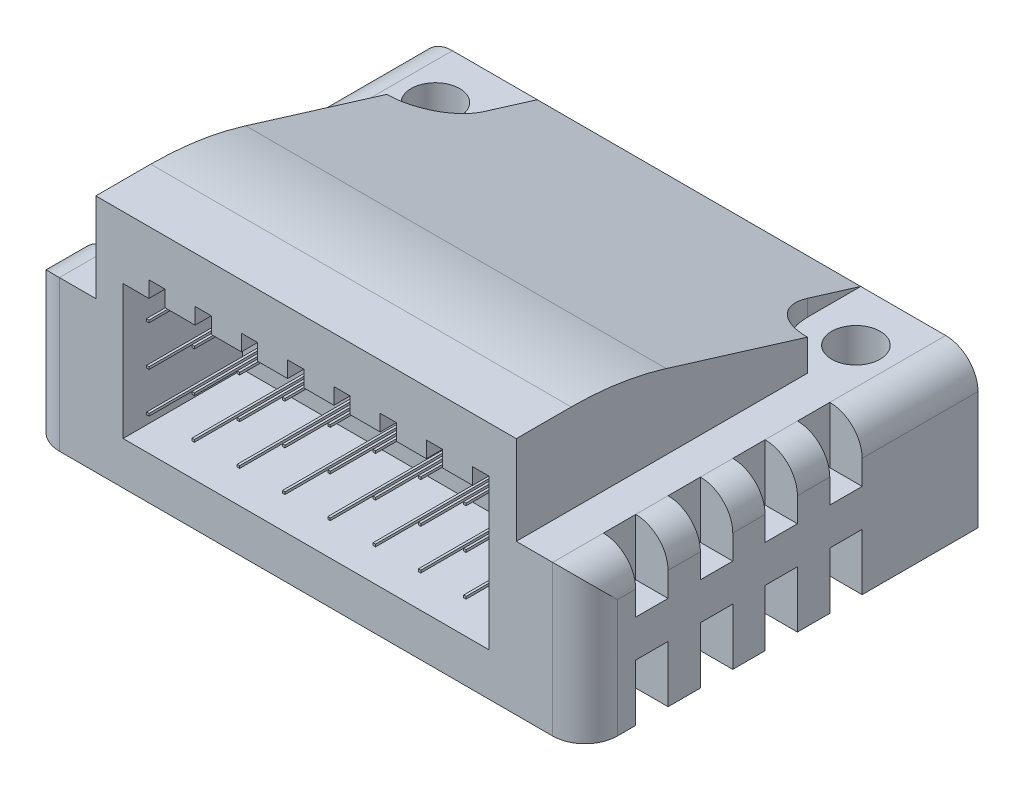
SolidWorks part; units mm, degrees
ref_plane "Front Plane" through (0, 0, 0) normal (0, 0, 1) x (1, 0, 0)
ref_plane "Top Plane" through (0, 0, 0) normal (0, 1, 0) x (1, 0, 0)
ref_plane "Right Plane" through (0, 0, 0) normal (1, 0, 0) x (0, 0, -1)
sketch "Sketch1" plane through (0, 0, 0) normal (0, 1, 0) x (1, 0, 0)
  line L1 (17.25, -12.15) -> (-17.25, -12.15)
  line L2 (17.25, -12.15) -> (17.25, 12.15)
  line L3 (17.25, 12.15) -> (-17.25, 12.15)
  line L4 (-17.25, -12.15) -> (-17.25, 12.15)
  line L5 (17.25, -12.15) -> (-17.25, 12.15) construction
  line L6 (17.25, 12.15) -> (-17.25, -12.15) construction
  point P0 (0, 0)
  dimension "D1" = 34.5
  dimension "D2" = 24.3
extrude "Boss-Extrude1" add sketch "Sketch1" along normal blind 9.3
ref_plane "Plane1" through (13, 0, 0) normal (1, 0, 0) x (0, 0, -1)
sketch "Sketch2" plane through (13, 0, 0) normal (1, 0, 0) x (0, 0, -1)
  line L0 (-12.15, 9.3) -> (12.15, 9.3) construction
  line L1 (-12.15, 9.3) -> (12.15, 9.3)
  line L2 (-12.15, 9.3) -> (-12.15, 14.8)
  line L3 (-12.15, 14.8) -> (-5.75, 14.8)
  line L4 (-5.75, 14.8) -> (12.15, 9.3)
  line L5 (-12.15, 0) -> (12.15, 0) construction
  dimension "D1" = 14.8
  dimension "D2" = 6.4
extrude "Boss-Extrude2" add sketch "Sketch2" against normal offset from surface (26 mm away) 4.25 up to face at (-17.25, 4.65, 0)
fillet "Fillet1" radius 2 4 edges at (17.25, 4.65, 12.15) (-17.25, 4.65, 12.15) (-17.25, 9.3, 0) (17.25, 9.3, 0)
fillet "Fillet2" radius 20 1 edges at (0, 14.8, 5.75)
sketch "Sketch4" plane through (17.25, 0, 0) normal (1, 0, 0) x (0, 0, -1)
  line L0 (-12.15, 0) -> (-12.15, 9.3) construction
  line L1 (-12.15, 0) -> (-12.15, 9.3)
  line L2 (-12.15, 9.3) -> (12.15, 9.3) construction
  line L3 (-12.15, 9.3) -> (12.15, 9.3)
  line L4 (12.15, 7.3) -> (12.15, 9.3) construction
  line L5 (12.15, 7.3) -> (12.15, 0) construction
  line L6 (-10.15, 0) -> (12.15, 0) construction
  line L7 (-12.15, 0) -> (-10.15, 0) construction
  line L8 (12.15, 7.3) -> (12.15, 9.3)
  line L9 (12.15, 7.3) -> (12.15, 0)
  line L10 (-10.15, 0) -> (12.15, 0)
  line L11 (-12.15, 0) -> (-10.15, 0)
  line L12 (-12.15, 4.65) -> (12.15, 4.65) construction
  line L13 (-9.0144, 9.3) -> (-9.0144, 5.8)
  line L14 (-9.0144, 5.8) -> (-7.0144, 5.8)
  line L15 (-7.0144, 5.8) -> (-7.0144, 9.3)
  line L16 (-5.0144, 9.3) -> (-5.0144, 5.8)
  line L17 (-5.0144, 5.8) -> (-3.0144, 5.8)
  line L18 (-3.0144, 5.8) -> (-3.0144, 9.3)
  line L19 (-1.0144, 9.3) -> (-1.0144, 5.8)
  line L20 (-1.0144, 5.8) -> (0.9856, 5.8)
  line L21 (0.9856, 5.8) -> (0.9856, 9.3)
  line L22 (2.9856, 9.3) -> (2.9856, 5.8)
  line L23 (2.9856, 5.8) -> (4.9856, 5.8)
  line L24 (4.9856, 5.8) -> (4.9856, 9.3)
  line L25 (4.9856, 3.5) -> (4.9856, 0)
  line L26 (2.9856, 3.5) -> (4.9856, 3.5)
  line L27 (2.9856, 0) -> (2.9856, 3.5)
  line L28 (0.9856, 3.5) -> (0.9856, 0)
  line L29 (-1.0144, 3.5) -> (0.9856, 3.5)
  line L30 (-1.0144, 0) -> (-1.0144, 3.5)
  line L31 (-3.0144, 3.5) -> (-3.0144, 0)
  line L32 (-5.0144, 3.5) -> (-3.0144, 3.5)
  line L33 (-5.0144, 0) -> (-5.0144, 3.5)
  line L34 (-7.0144, 3.5) -> (-7.0144, 0)
  line L35 (-9.0144, 3.5) -> (-7.0144, 3.5)
  line L36 (-9.0144, 0) -> (-9.0144, 3.5)
  line M14 (12.15, 7.3) -> (-10.15, 7.3)
  dimension "D1" = 2
  dimension "D2" = 3.5
  dimension "D3" = 4
extrude "Cut-Extrude1" cut sketch "Sketch4" against normal blind 2 contours L15 L3 L13 M14 | L14 L15 L13 M14 | L18 L3 L16 M14 | L17 L18 L16 M14 | L21 L3 L19 M14 | L20 L21 L19 M14 | L24 L3 L22 M14 | L23 L24 L22 M14 | L36 L10 L34 L35 | L33 L10 L31 L32 | L30 L10 L28 L29 | L27 L10 L25 L26
sketch "Sketch5" plane through (-17.25, 0, 0) normal (-1, 0, 0) x (0, 0, 1)
  line L0 (9.0144, 0) -> (9.0144, 3.5) construction
  line L1 (9.0144, 3.5) -> (7.0144, 3.5) construction
  line L2 (7.0144, 3.5) -> (7.0144, 0) construction
  line L3 (5.0144, 0) -> (5.0144, 3.5) construction
  line L4 (5.0144, 3.5) -> (3.0144, 3.5) construction
  line L5 (3.0144, 3.5) -> (3.0144, 0) construction
  line L6 (1.0144, 0) -> (1.0144, 3.5) construction
  line L7 (1.0144, 3.5) -> (-0.9856, 3.5) construction
  line L8 (-0.9856, 3.5) -> (-0.9856, 0) construction
  line L9 (-2.9856, 0) -> (-2.9856, 3.5) construction
  line L10 (-4.9856, 3.5) -> (-4.9856, 0) construction
  line L11 (-2.9856, 3.5) -> (-4.9856, 3.5) construction
  line L12 (-2.9856, 5.8) -> (-4.9856, 5.8) construction
  line L13 (-4.9856, 5.8) -> (-4.9856, 9.3) construction
  line L14 (-2.9856, 9.3) -> (-2.9856, 5.8) construction
  line L15 (1.0144, 5.8) -> (-0.9856, 5.8) construction
  line L16 (-0.9856, 5.8) -> (-0.9856, 9.3) construction
  line L17 (1.0144, 9.3) -> (1.0144, 5.8) construction
  line L18 (5.0144, 5.8) -> (3.0144, 5.8) construction
  line L19 (3.0144, 5.8) -> (3.0144, 9.3) construction
  line L20 (5.0144, 9.3) -> (5.0144, 5.8) construction
  line L21 (7.0144, 5.8) -> (7.0144, 9.3) construction
  line L22 (9.0144, 5.8) -> (7.0144, 5.8) construction
  line L23 (9.0144, 9.3) -> (9.0144, 5.8) construction
  line L24 (12.15, 0) -> (12.15, 9.3) construction
  line L25 (12.15, 0) -> (10.15, 0) construction
  line L26 (10.15, 0) -> (-12.15, 0) construction
  line L27 (-12.15, 7.3) -> (-12.15, 0) construction
  line L28 (-12.15, 7.3) -> (-12.15, 9.3) construction
  line L29 (12.15, 9.3) -> (-12.15, 9.3) construction
  line L30 (9.0144, 0) -> (9.0144, 3.5)
  line L31 (9.0144, 3.5) -> (7.0144, 3.5)
  line L32 (7.0144, 3.5) -> (7.0144, 0)
  line L33 (5.0144, 0) -> (5.0144, 3.5)
  line L34 (5.0144, 3.5) -> (3.0144, 3.5)
  line L35 (3.0144, 3.5) -> (3.0144, 0)
  line L36 (1.0144, 0) -> (1.0144, 3.5)
  line L37 (1.0144, 3.5) -> (-0.9856, 3.5)
  line L38 (-0.9856, 3.5) -> (-0.9856, 0)
  line L39 (-2.9856, 0) -> (-2.9856, 3.5)
  line L40 (-4.9856, 3.5) -> (-4.9856, 0)
  line L41 (-2.9856, 3.5) -> (-4.9856, 3.5)
  line L42 (-2.9856, 5.8) -> (-4.9856, 5.8)
  line L43 (-4.9856, 5.8) -> (-4.9856, 9.3)
  line L44 (-2.9856, 9.3) -> (-2.9856, 5.8)
  line L45 (1.0144, 5.8) -> (-0.9856, 5.8)
  line L46 (-0.9856, 5.8) -> (-0.9856, 9.3)
  line L47 (1.0144, 9.3) -> (1.0144, 5.8)
  line L48 (5.0144, 5.8) -> (3.0144, 5.8)
  line L49 (3.0144, 5.8) -> (3.0144, 9.3)
  line L50 (5.0144, 9.3) -> (5.0144, 5.8)
  line L51 (7.0144, 5.8) -> (7.0144, 9.3)
  line L52 (9.0144, 5.8) -> (7.0144, 5.8)
  line L53 (9.0144, 9.3) -> (9.0144, 5.8)
  line L54 (12.15, 0) -> (12.15, 9.3)
  line L55 (12.15, 0) -> (10.15, 0)
  line L56 (10.15, 0) -> (-12.15, 0)
  line L57 (-12.15, 7.3) -> (-12.15, 0)
  line L58 (-12.15, 7.3) -> (-12.15, 9.3)
  line L59 (12.15, 9.3) -> (-12.15, 9.3)
  line M1 (-12.15, 0) -> (10.15, 0)
  line M3 (10.15, 7.3) -> (-12.15, 7.3)
extrude "Cut-Extrude2" cut sketch "Sketch5" against normal blind 2 contours L39 L41 L40 M1 | L37 L38 L36 M1 | L34 L35 L33 M1 | L31 L32 L30 M1 | L44 L59 L43 M3 | L44 L43 L42 M3 | L47 L59 L46 M3 | L47 L46 L45 M3 | L50 L59 L49 M3 | L50 L49 L48 M3 | L53 L59 L51 M3 | L53 L51 L52 M3
sketch "Sketch6" plane through (0, 0, 12.15) normal (0, 0, 1) x (1, 0, 0)
  line L0 (0, 14.8) -> (0, 0) construction
  line L1 (-13, 14.8) -> (13, 14.8) construction
  line L2 (-6.855, 10.95) -> (-6.855, 11.95)
  line L3 (12.315, 1.65) -> (-12.315, 1.65)
  line L4 (12.315, 1.65) -> (12.315, 13.15)
  line L5 (12.315, 13.15) -> (-12.315, 13.15)
  line L6 (-12.315, 1.65) -> (-12.315, 13.15)
  line L7 (12.315, 1.65) -> (-12.315, 13.15) construction
  line L8 (12.315, 13.15) -> (-12.315, 1.65) construction
  line L9 (-11.315, 10.95) -> (-9.715, 10.95)
  line L10 (-11.315, 10.95) -> (-11.315, 2.65)
  line L11 (-11.315, 2.65) -> (11.315, 2.65)
  line L12 (11.315, 10.95) -> (11.315, 2.65)
  line L14 (-9.715, 10.95) -> (-9.715, 11.95)
  line L15 (-9.715, 11.95) -> (-8.715, 11.95)
  line L16 (-8.715, 10.95) -> (-8.715, 11.95)
  line L17 (-6.855, 11.95) -> (-5.855, 11.95)
  line L18 (-5.855, 10.95) -> (-5.855, 11.95)
  line L19 (-3.995, 10.95) -> (-3.995, 11.95)
  line L20 (-3.995, 11.95) -> (-2.995, 11.95)
  line L21 (-2.995, 10.95) -> (-2.995, 11.95)
  line L22 (-1.135, 10.95) -> (-1.135, 11.95)
  line L23 (-1.135, 11.95) -> (-0.135, 11.95)
  line L24 (-0.135, 10.95) -> (-0.135, 11.95)
  line L25 (1.725, 10.95) -> (1.725, 11.95)
  line L26 (1.725, 11.95) -> (2.725, 11.95)
  line L27 (2.725, 10.95) -> (2.725, 11.95)
  line L28 (4.585, 10.95) -> (4.585, 11.95)
  line L29 (4.585, 11.95) -> (5.585, 11.95)
  line L30 (5.585, 10.95) -> (5.585, 11.95)
  line L31 (7.445, 10.95) -> (7.445, 11.95)
  line L32 (7.445, 11.95) -> (8.445, 11.95)
  line L33 (8.445, 10.95) -> (8.445, 11.95)
  line L34 (10.305, 10.95) -> (10.305, 11.95)
  line L35 (10.305, 11.95) -> (11.305, 11.95)
  line L36 (11.305, 10.95) -> (11.305, 11.95)
  line L37 (-8.715, 10.95) -> (-6.855, 10.95)
  line L38 (-5.855, 10.95) -> (-3.995, 10.95)
  line L39 (-2.995, 10.95) -> (-1.135, 10.95)
  line L40 (-0.135, 10.95) -> (1.725, 10.95)
  line L41 (2.725, 10.95) -> (4.585, 10.95)
  line L42 (5.585, 10.95) -> (7.6032, 10.95)
  line L43 (8.445, 10.95) -> (10.305, 10.95)
  line L44 (11.305, 10.95) -> (11.315, 10.95)
  point P5 (0, 7.4)
  dimension "D1" = 24.63
  dimension "D2" = 11.5
  dimension "D3" = 2.2
  dimension "D4" = 1
  dimension "D5" = 1
  dimension "D6" = 1
  dimension "D7" = 1.6
  dimension "D8" = 1
  dimension "D9" = 1
  dimension "D10" = 8
extrude "Cut-Extrude4" cut sketch "Sketch6" against normal blind 7.4
sketch "Sketch8" plane through (0, 0, 4.75) normal (0, 0, 1) x (1, 0, 0)
  line L0 (11.315, 10.95) -> (11.315, 2.65) construction
  line L1 (9.745, 9.8) -> (9.895, 9.8)
  line L2 (9.745, 9.8) -> (9.745, 9.65)
  line L3 (9.745, 9.65) -> (9.895, 9.65)
  line L4 (9.895, 9.8) -> (9.895, 9.65)
  line L5 (9.745, 9.8) -> (9.895, 9.65) construction
  line L6 (9.745, 9.65) -> (9.895, 9.8) construction
  line L7 (8.445, 10.95) -> (10.305, 10.95) construction
  line L8 (9.745, 7.3) -> (9.745, 7.15)
  line L9 (9.745, 7.3) -> (9.895, 7.3)
  line L10 (9.895, 7.3) -> (9.895, 7.15)
  line L11 (9.745, 7.15) -> (9.895, 7.15)
  line L12 (9.745, 4.8) -> (9.745, 4.65)
  line L13 (9.745, 4.8) -> (9.895, 4.8)
  line L14 (9.895, 4.8) -> (9.895, 4.65)
  line L15 (9.745, 4.65) -> (9.895, 4.65)
  line L16 (6.945, 9.8) -> (7.095, 9.8)
  line L17 (6.945, 9.8) -> (6.945, 9.65)
  line L18 (7.095, 9.8) -> (7.095, 9.65)
  line L19 (6.945, 9.65) -> (7.095, 9.65)
  line L20 (6.945, 7.3) -> (6.945, 7.15)
  line L21 (6.945, 7.3) -> (7.095, 7.3)
  line L22 (7.095, 7.3) -> (7.095, 7.15)
  line L23 (6.945, 7.15) -> (7.095, 7.15)
  line L24 (6.945, 4.8) -> (6.945, 4.65)
  line L25 (6.945, 4.8) -> (7.095, 4.8)
  line L26 (7.095, 4.8) -> (7.095, 4.65)
  line L27 (6.945, 4.65) -> (7.095, 4.65)
  line L28 (4.145, 9.8) -> (4.295, 9.8)
  line L29 (4.145, 9.8) -> (4.145, 9.65)
  line L30 (4.295, 9.8) -> (4.295, 9.65)
  line L31 (4.145, 9.65) -> (4.295, 9.65)
  line L32 (4.145, 7.3) -> (4.145, 7.15)
  line L33 (4.145, 7.3) -> (4.295, 7.3)
  line L34 (4.295, 7.3) -> (4.295, 7.15)
  line L35 (4.145, 7.15) -> (4.295, 7.15)
  line L36 (4.145, 4.8) -> (4.145, 4.65)
  line L37 (4.145, 4.8) -> (4.295, 4.8)
  line L38 (4.295, 4.8) -> (4.295, 4.65)
  line L39 (4.145, 4.65) -> (4.295, 4.65)
  line L40 (1.345, 9.8) -> (1.495, 9.8)
  line L41 (1.345, 9.8) -> (1.345, 9.65)
  line L42 (1.495, 9.8) -> (1.495, 9.65)
  line L43 (1.345, 9.65) -> (1.495, 9.65)
  line L44 (1.345, 7.3) -> (1.345, 7.15)
  line L45 (1.345, 7.3) -> (1.495, 7.3)
  line L46 (1.495, 7.3) -> (1.495, 7.15)
  line L47 (1.345, 7.15) -> (1.495, 7.15)
  line L48 (1.345, 4.8) -> (1.345, 4.65)
  line L49 (1.345, 4.8) -> (1.495, 4.8)
  line L50 (1.495, 4.8) -> (1.495, 4.65)
  line L51 (1.345, 4.65) -> (1.495, 4.65)
  line L52 (-1.455, 9.8) -> (-1.305, 9.8)
  line L53 (-1.455, 9.8) -> (-1.455, 9.65)
  line L54 (-1.305, 9.8) -> (-1.305, 9.65)
  line L55 (-1.455, 9.65) -> (-1.305, 9.65)
  line L56 (-1.455, 7.3) -> (-1.455, 7.15)
  line L57 (-1.455, 7.3) -> (-1.305, 7.3)
  line L58 (-1.305, 7.3) -> (-1.305, 7.15)
  line L59 (-1.455, 7.15) -> (-1.305, 7.15)
  line L60 (-1.455, 4.8) -> (-1.455, 4.65)
  line L61 (-1.455, 4.8) -> (-1.305, 4.8)
  line L62 (-1.305, 4.8) -> (-1.305, 4.65)
  line L63 (-1.455, 4.65) -> (-1.305, 4.65)
  line L64 (-4.255, 9.8) -> (-4.105, 9.8)
  line L65 (-4.255, 9.8) -> (-4.255, 9.65)
  line L66 (-4.105, 9.8) -> (-4.105, 9.65)
  line L67 (-4.255, 9.65) -> (-4.105, 9.65)
  line L68 (-4.255, 7.3) -> (-4.255, 7.15)
  line L69 (-4.255, 7.3) -> (-4.105, 7.3)
  line L70 (-4.105, 7.3) -> (-4.105, 7.15)
  line L71 (-4.255, 7.15) -> (-4.105, 7.15)
  line L72 (-4.255, 4.8) -> (-4.255, 4.65)
  line L73 (-4.255, 4.8) -> (-4.105, 4.8)
  line L74 (-4.105, 4.8) -> (-4.105, 4.65)
  line L75 (-4.255, 4.65) -> (-4.105, 4.65)
  line L76 (-7.055, 9.8) -> (-6.905, 9.8)
  line L77 (-7.055, 9.8) -> (-7.055, 9.65)
  line L78 (-6.905, 9.8) -> (-6.905, 9.65)
  line L79 (-7.055, 9.65) -> (-6.905, 9.65)
  line L80 (-7.055, 7.3) -> (-7.055, 7.15)
  line L81 (-7.055, 7.3) -> (-6.905, 7.3)
  line L82 (-6.905, 7.3) -> (-6.905, 7.15)
  line L83 (-7.055, 7.15) -> (-6.905, 7.15)
  line L84 (-7.055, 4.8) -> (-7.055, 4.65)
  line L85 (-7.055, 4.8) -> (-6.905, 4.8)
  line L86 (-6.905, 4.8) -> (-6.905, 4.65)
  line L87 (-7.055, 4.65) -> (-6.905, 4.65)
  line L88 (-9.855, 9.8) -> (-9.705, 9.8)
  line L89 (-9.855, 9.8) -> (-9.855, 9.65)
  line L90 (-9.705, 9.8) -> (-9.705, 9.65)
  line L91 (-9.855, 9.65) -> (-9.705, 9.65)
  line L92 (-9.855, 7.3) -> (-9.855, 7.15)
  line L93 (-9.855, 7.3) -> (-9.705, 7.3)
  line L94 (-9.705, 7.3) -> (-9.705, 7.15)
  line L95 (-9.855, 7.15) -> (-9.705, 7.15)
  line L96 (-9.855, 4.8) -> (-9.855, 4.65)
  line L97 (-9.855, 4.8) -> (-9.705, 4.8)
  line L98 (-9.705, 4.8) -> (-9.705, 4.65)
  line L99 (-9.855, 4.65) -> (-9.705, 4.65)
  point P0 (9.82, 9.725)
  dimension "D1" = 0.15
  dimension "D2" = 0.15
  dimension "D3" = 1.42
  dimension "D4" = 1.15
  dimension "D5" = 3
  dimension "D6" = 8
extrude "Boss-Extrude3" add sketch "Sketch8" along normal blind 7.4
sketch "Sketch9" plane through (0, 9.3, 0) normal (0, 1, 0) x (1, 0, 0)
  line L0 (13, -12.15) -> (13, 12.15) construction
  line L1 (-13, 12.15) -> (-13, -12.15) construction
  line L2 (13, -12.15) -> (15.25, -12.15) construction
  line L3 (-15.25, -12.15) -> (-13, -12.15) construction
  circle A0 centre (13, 8.85) radius 1.5
  circle A1 centre (-13, 8.85) radius 1.5
  dimension "D2" = 3
  dimension "D3" = 3
  dimension "D1" = 21
  dimension "D4" = 21
extrude "Cut-Extrude5" cut sketch "Sketch9" against normal through all and the other way through all
sketch "Sketch10" plane through (0, 9.3, 0) normal (0, 1, 0) x (1, 0, 0)
  line L0 (-10, 8.85) -> (-10, 12.15)
  line L1 (-13, 12.15) -> (13, 12.15) construction
  line L2 (-10, 12.15) -> (-13, 12.15)
  line L3 (-13, 12.15) -> (-13, 11.85)
  line L4 (10, 8.85) -> (10, 12.15)
  line L5 (10, 12.15) -> (13, 12.15)
  line L6 (13, 12.15) -> (13, 11.85)
  arc A0 (10, 8.85) -> (13, 11.85) centre (13, 8.85) ccw
  arc A1 (-13, 11.85) -> (-10, 8.85) centre (-13, 8.85) ccw
  dimension "D1" = 6
  dimension "D2" = 6
extrude "Cut-Extrude6" cut sketch "Sketch10" along normal through all
sketch "Sketch11" plane through (0, 0, -12.15) normal (0, 0, -1) x (-1, 0, 0)
  line L0 (-17.25, 3.65) -> (17.25, 3.65) construction
  line L1 (-17.25, 7.3) -> (-17.25, 0) construction
  line L2 (17.25, 7.3) -> (17.25, 0) construction
  line L4 (7.75, 8.65) -> (-7.75, 8.65)
  line L5 (7.75, 8.65) -> (7.75, 3.65)
  line L6 (7.75, 3.65) -> (-7.75, 3.65)
  line L7 (-7.75, 8.65) -> (-7.75, 3.65)
  line L8 (7.75, 8.65) -> (-7.75, 3.65) construction
  line L9 (7.75, 3.65) -> (-7.75, 8.65) construction
  point P6 (0, 6.15)
  dimension "D1" = 5
  dimension "D2" = 15.5
extrude "Cut-Extrude7" cut sketch "Sketch11" against normal blind 10
sketch "Sketch12" plane through (0, 0, -2.15) normal (0, 0, -1) x (-1, 0, 0)
  line L0 (0, 8.65) -> (0, 3.65) construction
  line L1 (7.75, 8.65) -> (-7.75, 8.65) construction
  line L2 (-7.75, 3.65) -> (7.75, 3.65) construction
  line L3 (-7.6931, 8.5523) -> (7.6931, 8.5523)
  line L4 (7.6931, 8.5523) -> (7.6931, 5.7523)
  line L5 (7.6931, 5.7523) -> (7.4, 5.7523)
  line L6 (7.4, 5.7523) -> (7.4, 4.2679)
  line L7 (7.4, 4.2679) -> (6.8844, 3.7523)
  line L8 (6.8844, 3.7523) -> (-6.8844, 3.7523)
  line L9 (-4.4, 8.4523) -> (4.4, 8.4523)
  line L10 (4.4, 8.4523) -> (4.4, 6.9523)
  line L11 (4.4, 6.9523) -> (3.4299, 6.9523)
  line L12 (3.4299, 6.9523) -> (3.2156, 7.1523)
  line L13 (3.2156, 7.1523) -> (-3.2156, 7.1523)
  line L14 (-5.75, 8.0552) -> (-5.75, 7.5052)
  line L23 (4.75, 8.0552) -> (5.75, 8.0552)
  line L24 (4.75, 8.0552) -> (4.75, 7.5052)
  line L25 (4.75, 7.5052) -> (5.75, 7.5052)
  line L26 (5.75, 8.0552) -> (5.75, 7.5052)
  line L27 (6.2, 8.0552) -> (7.2, 8.0552)
  line L28 (6.2, 8.0552) -> (6.2, 7.5052)
  line L29 (6.2, 7.5052) -> (7.2, 7.5052)
  line L30 (7.2, 8.0552) -> (7.2, 7.5052)
  line L31 (-4.75, 8.0552) -> (-5.75, 8.0552)
  line L32 (-4.75, 8.0552) -> (-4.75, 7.5052)
  line L33 (-4.75, 7.5052) -> (-5.75, 7.5052)
  line L34 (-7.2, 8.0552) -> (-7.2, 7.5052)
  line L35 (-6.2, 8.0552) -> (-7.2, 8.0552)
  line L36 (-6.2, 8.0552) -> (-6.2, 7.5052)
  line L37 (-6.2, 7.5052) -> (-7.2, 7.5052)
  line L38 (-7.6931, 8.5523) -> (-7.6931, 5.7523)
  line L39 (-7.6931, 5.7523) -> (-7.4, 5.7523)
  line L40 (-7.4, 5.7523) -> (-7.4, 4.2679)
  line L41 (-3.4299, 6.9523) -> (-3.2156, 7.1523)
  line L42 (-7.4, 4.2679) -> (-6.8844, 3.7523)
  line L43 (-4.4, 6.9523) -> (-3.4299, 6.9523)
  line L44 (-4.4, 8.4523) -> (-4.4, 6.9523)
  point P8 (0, 8.5523)
  point P13 (0, 7.1523)
  point P42 (0, 3.7523)
  point P44 (0, 8.4523)
  dimension "D1" = 135
  dimension "D2" = 7.4
  dimension "D3" = 3.2
  dimension "D4" = 4.4
  dimension "D5" = 2
  dimension "D6" = 4.8
  dimension "D7" = 1.5
  dimension "D8" = 0.35
  dimension "D9" = 1
  dimension "D10" = 1.3
  dimension "D11" = 0.55
  dimension "D12" = 1
  dimension "D13" = 0.45
extrude "Boss-Extrude4" add sketch "Sketch12" along normal blind 10
sketch "Sketch13" plane through (0, 0, -12.15) normal (0, 0, -1) x (-1, 0, 0)
  line L0 (0, 3.7523) -> (0, 8.4523) construction
  line L1 (-6.8844, 3.7523) -> (6.8844, 3.7523) construction
  line L2 (4.4, 8.4523) -> (-4.4, 8.4523) construction
  line L3 (-0.21, 6.7153) -> (0.21, 6.7153)
  line L4 (5.68, 6.7153) -> (5.68, 6.9253)
  line L5 (5.68, 6.9253) -> (5.9, 6.9253)
  line L6 (5.9, 6.9253) -> (5.9, 6.7153)
  line L7 (5.9, 6.7153) -> (6.4, 6.7153)
  line L8 (6.4, 6.7153) -> (6.4, 7.2153)
  line L9 (6.4, 7.2153) -> (6.8, 7.2153)
  line L10 (6.8, 7.2153) -> (6.8, 4.2153)
  line L11 (6.8, 4.2153) -> (-6.8, 4.2153)
  line L12 (0.41, 6.7153) -> (0.41, 6.3453)
  line L13 (3.4299, 6.9523) -> (4.4, 6.9523) construction
  line L14 (0.21, 6.7153) -> (0.21, 6.3453)
  line L15 (0.21, 6.3453) -> (0.31, 6.3453)
  line L16 (0.31, 6.3453) -> (0.31, 6.7153)
  line L17 (0.51, 6.3453) -> (0.51, 6.7153)
  line L18 (0.41, 6.3453) -> (0.51, 6.3453)
  line L19 (0.31, 6.7153) -> (0.41, 6.7153)
  line L20 (0.51, 6.7153) -> (1.41, 6.7153)
  line L21 (1.41, 6.7153) -> (1.41, 6.3453)
  line L22 (1.51, 6.3453) -> (1.51, 6.7153)
  line L23 (1.41, 6.3453) -> (1.51, 6.3453)
  line L24 (1.61, 6.7153) -> (1.61, 6.3453)
  line L25 (1.61, 6.3453) -> (1.71, 6.3453)
  line L26 (1.71, 6.3453) -> (1.71, 6.7153)
  line L27 (2.61, 6.7153) -> (2.61, 6.3453)
  line L28 (2.71, 6.3453) -> (2.71, 6.7153)
  line L29 (2.61, 6.3453) -> (2.71, 6.3453)
  line L30 (2.81, 6.7153) -> (2.81, 6.3453)
  line L31 (2.81, 6.3453) -> (2.91, 6.3453)
  line L32 (2.91, 6.3453) -> (2.91, 6.7153)
  line L33 (3.81, 6.7153) -> (3.81, 6.3453)
  line L34 (3.91, 6.3453) -> (3.91, 6.7153)
  line L35 (3.81, 6.3453) -> (3.91, 6.3453)
  line L36 (4.01, 6.7153) -> (4.01, 6.3453)
  line L37 (4.01, 6.3453) -> (4.11, 6.3453)
  line L38 (4.11, 6.3453) -> (4.11, 6.7153)
  line L39 (5.01, 6.7153) -> (5.01, 6.3453)
  line L40 (5.11, 6.3453) -> (5.11, 6.7153)
  line L41 (5.01, 6.3453) -> (5.11, 6.3453)
  line L42 (5.21, 6.7153) -> (5.21, 6.3453)
  line L43 (5.21, 6.3453) -> (5.31, 6.3453)
  line L44 (5.31, 6.3453) -> (5.31, 6.7153)
  line L45 (1.51, 6.7153) -> (1.61, 6.7153)
  line L46 (1.71, 6.7153) -> (2.61, 6.7153)
  line L47 (2.71, 6.7153) -> (2.81, 6.7153)
  line L48 (2.91, 6.7153) -> (3.81, 6.7153)
  line L49 (3.91, 6.7153) -> (4.01, 6.7153)
  line L50 (4.11, 6.7153) -> (5.01, 6.7153)
  line L51 (5.11, 6.7153) -> (5.21, 6.7153)
  line L52 (5.31, 6.7153) -> (5.68, 6.7153)
  line L53 (-6.8, 7.2153) -> (-6.8, 4.2153)
  line L54 (-6.4, 7.2153) -> (-6.8, 7.2153)
  line L55 (-6.4, 6.7153) -> (-6.4, 7.2153)
  line L56 (-5.9, 6.7153) -> (-6.4, 6.7153)
  line L57 (-5.9, 6.9253) -> (-5.9, 6.7153)
  line L58 (-5.68, 6.9253) -> (-5.9, 6.9253)
  line L59 (-5.68, 6.7153) -> (-5.68, 6.9253)
  line L60 (-5.31, 6.7153) -> (-5.68, 6.7153)
  line L61 (-5.31, 6.3453) -> (-5.31, 6.7153)
  line L62 (-5.21, 6.3453) -> (-5.31, 6.3453)
  line L63 (-5.21, 6.7153) -> (-5.21, 6.3453)
  line L64 (-5.11, 6.7153) -> (-5.21, 6.7153)
  line L65 (-5.11, 6.3453) -> (-5.11, 6.7153)
  line L66 (-5.01, 6.3453) -> (-5.11, 6.3453)
  line L67 (-5.01, 6.7153) -> (-5.01, 6.3453)
  line L68 (-4.11, 6.7153) -> (-5.01, 6.7153)
  line L69 (-4.11, 6.3453) -> (-4.11, 6.7153)
  line L70 (-4.01, 6.3453) -> (-4.11, 6.3453)
  line L71 (-4.01, 6.7153) -> (-4.01, 6.3453)
  line L72 (-3.91, 6.7153) -> (-4.01, 6.7153)
  line L73 (-3.91, 6.3453) -> (-3.91, 6.7153)
  line L74 (-3.81, 6.3453) -> (-3.91, 6.3453)
  line L75 (-3.81, 6.7153) -> (-3.81, 6.3453)
  line L76 (-2.91, 6.7153) -> (-3.81, 6.7153)
  line L77 (-2.91, 6.3453) -> (-2.91, 6.7153)
  line L78 (-2.81, 6.3453) -> (-2.91, 6.3453)
  line L79 (-2.81, 6.7153) -> (-2.81, 6.3453)
  line L80 (-2.71, 6.7153) -> (-2.81, 6.7153)
  line L81 (-2.71, 6.3453) -> (-2.71, 6.7153)
  line L82 (-2.61, 6.3453) -> (-2.71, 6.3453)
  line L83 (-2.61, 6.7153) -> (-2.61, 6.3453)
  line L84 (-1.71, 6.7153) -> (-2.61, 6.7153)
  line L85 (-1.71, 6.3453) -> (-1.71, 6.7153)
  line L86 (-1.61, 6.3453) -> (-1.71, 6.3453)
  line L87 (-1.61, 6.7153) -> (-1.61, 6.3453)
  line L88 (-1.51, 6.7153) -> (-1.61, 6.7153)
  line L89 (-1.51, 6.3453) -> (-1.51, 6.7153)
  line L90 (-1.41, 6.3453) -> (-1.51, 6.3453)
  line L91 (-1.41, 6.7153) -> (-1.41, 6.3453)
  line L92 (-0.51, 6.7153) -> (-1.41, 6.7153)
  line L93 (-0.51, 6.3453) -> (-0.51, 6.7153)
  line L94 (-0.41, 6.3453) -> (-0.51, 6.3453)
  line L95 (-0.41, 6.7153) -> (-0.41, 6.3453)
  line L96 (-0.31, 6.7153) -> (-0.41, 6.7153)
  line L97 (-0.31, 6.3453) -> (-0.31, 6.7153)
  line L98 (-0.21, 6.3453) -> (-0.31, 6.3453)
  line L99 (-0.21, 6.7153) -> (-0.21, 6.3453)
  point P59 (0, 4.2153)
  point P106 (0, 6.7153)
  dimension "D1" = 0.22
  dimension "D2" = 0.21
  dimension "D3" = 0.21
  dimension "D4" = 0.5
  dimension "D5" = 0.5
  dimension "D6" = 0.4
  dimension "D7" = 6.8
  dimension "D8" = 3
  dimension "D9" = 0.237
  dimension "D10" = 0.21
  dimension "D11" = 0.1
  dimension "D12" = 0.37
  dimension "D13" = 2
  dimension "D14" = 5
extrude "Cut-Extrude8" cut sketch "Sketch13" against normal blind 10
sketch "Sketch14" plane through (0, 0, -12.15) normal (0, 0, -1) x (-1, 0, 0)
  line L0 (-6.8, 4.2153) -> (6.8, 4.2153) construction
  line L1 (5.1, 4.2153) -> (5.4, 4.2153)
  line L2 (5.1, 4.2153) -> (5.1, 4.5153)
  line L3 (5.1, 4.5153) -> (5.4, 4.5153)
  line L4 (5.4, 4.2153) -> (5.4, 4.5153)
  line L5 (6.8, 4.2153) -> (6.8, 7.2153) construction
  line L6 (3.92, 4.2153) -> (3.92, 4.5153)
  line L7 (3.92, 4.5153) -> (4.22, 4.5153)
  line L8 (4.22, 4.2153) -> (4.22, 4.5153)
  line L9 (2.74, 4.2153) -> (2.74, 4.5153)
  line L10 (2.74, 4.5153) -> (3.04, 4.5153)
  line L11 (3.04, 4.2153) -> (3.04, 4.5153)
  line L12 (1.56, 4.2153) -> (1.56, 4.5153)
  line L13 (1.56, 4.5153) -> (1.86, 4.5153)
  line L14 (1.86, 4.2153) -> (1.86, 4.5153)
  line L15 (0.38, 4.2153) -> (0.38, 4.5153)
  line L16 (0.38, 4.5153) -> (0.68, 4.5153)
  line L17 (0.68, 4.2153) -> (0.68, 4.5153)
  line L18 (-0.8, 4.2153) -> (-0.8, 4.5153)
  line L19 (-0.8, 4.5153) -> (-0.5, 4.5153)
  line L20 (-0.5, 4.2153) -> (-0.5, 4.5153)
  line L21 (-1.98, 4.2153) -> (-1.98, 4.5153)
  line L22 (-1.98, 4.5153) -> (-1.68, 4.5153)
  line L23 (-1.68, 4.2153) -> (-1.68, 4.5153)
  line L24 (-3.16, 4.2153) -> (-3.16, 4.5153)
  line L25 (-3.16, 4.5153) -> (-2.86, 4.5153)
  line L26 (-2.86, 4.2153) -> (-2.86, 4.5153)
  line L27 (-4.34, 4.2153) -> (-4.34, 4.5153)
  line L28 (-4.34, 4.5153) -> (-4.04, 4.5153)
  line L29 (-4.04, 4.2153) -> (-4.04, 4.5153)
  line L30 (-5.52, 4.2153) -> (-5.52, 4.5153)
  line L31 (-5.52, 4.5153) -> (-5.22, 4.5153)
  line L32 (-5.22, 4.2153) -> (-5.22, 4.5153)
  line L33 (-5.52, 4.2153) -> (-5.22, 4.2153)
  line L34 (-4.34, 4.2153) -> (-4.04, 4.2153)
  line L35 (-3.16, 4.2153) -> (-2.86, 4.2153)
  line L36 (-1.98, 4.2153) -> (-1.68, 4.2153)
  line L37 (-0.8, 4.2153) -> (-0.5, 4.2153)
  line L38 (0.38, 4.2153) -> (0.68, 4.2153)
  line L39 (1.56, 4.2153) -> (1.86, 4.2153)
  line L40 (2.74, 4.2153) -> (3.04, 4.2153)
  line L41 (3.92, 4.2153) -> (4.22, 4.2153)
  dimension "D1" = 1.4
  dimension "D2" = 1.7
  dimension "D3" = 0.3
  dimension "D4" = 10
extrude "Boss-Extrude5" add sketch "Sketch14" against normal up to surface (10 mm away) up to face at (0, 6.5386, -2.15)
